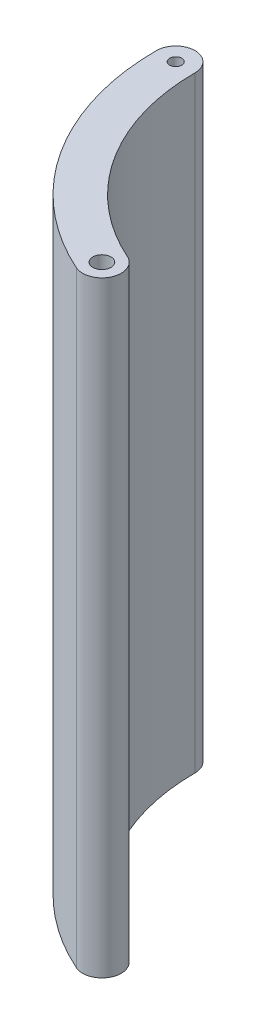
SolidWorks part; units mm, degrees
ref_plane "Plan de face" through (0, 0, 0) normal (0, 0, 1) x (1, 0, 0)
ref_plane "Plan de dessus" through (0, 0, 0) normal (0, 1, 0) x (1, 0, 0)
ref_plane "Plan de droite" through (0, 0, 0) normal (1, 0, 0) x (0, 0, -1)
sketch "Esquisse1" plane through (0, 0, 0) normal (0, 1, 0) x (1, 0, 0)
  arc A0 (-41.18, 0) -> (-16.7494, -37.6198) centre (0, 0) ccw
  arc A1 (-34.82, 0) -> (-14.1626, -31.8097) centre (0, 0) ccw
  arc A2 (-41.18, 0) -> (-34.82, 0) centre (-38, 0) cw
  arc A3 (-14.1626, -31.8097) -> (-16.7494, -37.6198) centre (-15.456, -34.7147) cw
  circle A4 centre (-38, 0) radius 1
  circle A5 centre (-15.456, -34.7147) radius 1.5
  dimension "D2" = 3.18
  dimension "D4" = 2
  dimension "D5" = 3
  dimension "D1" = 38
  dimension "D3" = 66
extrude "Boss.-Extru.1" add sketch "Esquisse1" along normal blind 100
